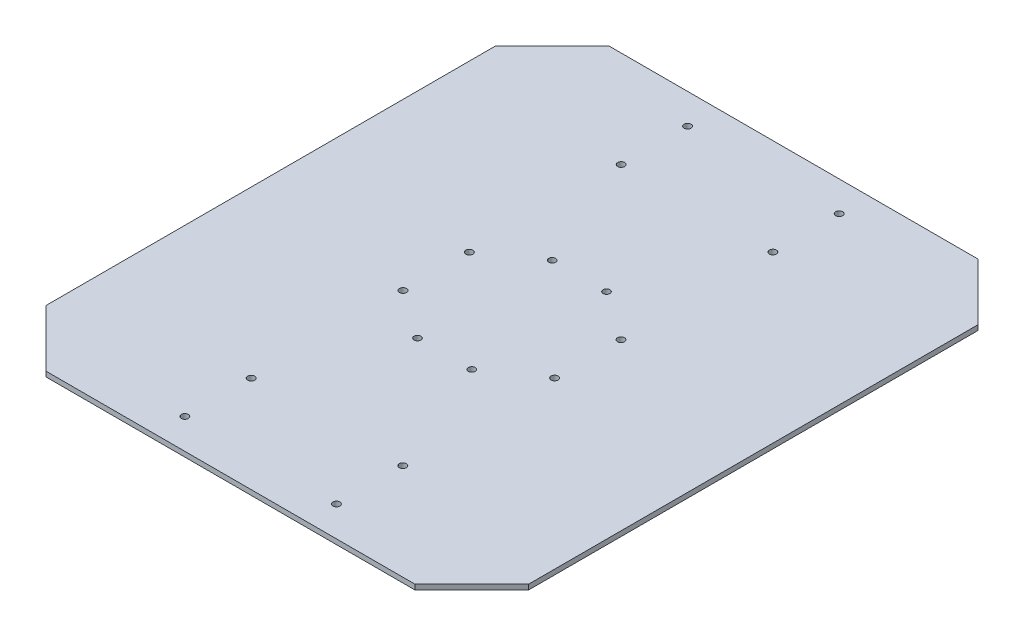
SolidWorks part; units mm, degrees
ref_plane "Front Plane" through (0, 0, 0) normal (0, 0, 1) x (1, 0, 0)
ref_plane "Top Plane" through (0, 0, 0) normal (0, 1, 0) x (1, 0, 0)
ref_plane "Right Plane" through (0, 0, 0) normal (1, 0, 0) x (0, 0, -1)
sketch "Sketch1" plane through (0, 0, 0) normal (0, 1, 0) x (1, 0, 0)
  line L0 (-121.2861, 87.138) -> (-85.365, 123.059)
  line L1 (-121.2861, 123.059) -> (183.5139, 123.059)
  line L2 (-121.2861, 123.059) -> (-121.2861, -232.541)
  line L3 (-121.2861, -232.541) -> (183.5139, -232.541)
  line L4 (183.5139, 123.059) -> (183.5139, -232.541)
  line L5 (31.1139, 95.069) -> (31.1139, -294.9418) construction
  line L6 (-146.0448, -54.741) -> (218.038, -54.741) construction
  line L7 (183.5139, 87.138) -> (147.5929, 123.059)
  line L8 (183.5139, -196.62) -> (147.5929, -232.541)
  line L9 (-121.2861, -196.62) -> (-85.365, -232.541)
  circle A0 centre (-16.7651, 104.009) radius 2.2225
  circle A1 centre (78.9929, 104.009) radius 2.2225
  circle A2 centre (-16.7651, 62.099) radius 2.2225
  circle A3 centre (78.9929, 62.099) radius 2.2225
  circle A4 centre (-16.7651, -171.581) radius 2.2225
  circle A5 centre (78.9929, -171.581) radius 2.2225
  circle A6 centre (78.9929, -213.491) radius 2.2225
  circle A7 centre (-16.7651, -213.491) radius 2.2225
  circle A8 centre (-16.7651, -33.786) radius 2.2225
  circle A9 centre (78.9929, -33.786) radius 2.2225
  circle A10 centre (78.9929, -75.696) radius 2.2225
  circle A11 centre (-16.7651, -75.696) radius 2.2225
  point P8 (31.1139, 123.059)
  point P11 (-121.2861, -54.741)
  point P42 (0, 0)
  point P43 (0, 0)
  point P44 (0, 0)
  point P45 (0, 0)
  point P46 (0, 0)
  point P47 (0, 0)
  dimension "D6" = 95.758
  dimension "D13" = 4.445
  dimension "D1" = 304.8
  dimension "D2" = 355.6
  dimension "D3" = 45
  dimension "D4" = 50.8
  dimension "D5" = 41.91
  dimension "D7" = 104.521
  dimension "D8" = 19.05
  dimension "D9" = 41.91
  dimension "D10" = 20.955
  dimension "D11" = 95.758
  dimension "D12" = 47.879
extrude "Boss-Extrude1" add sketch "Sketch1" along normal blind 3.175
sketch "Sketch2" plane through (0, 3.175, 0) normal (0, 1, 0) x (1, 0, 0)
  line L0 (31.1139, 123.059) -> (31.1139, -287.8465) construction
  line L1 (-85.365, 123.059) -> (147.5929, 123.059) construction
  line L2 (183.5139, -54.741) -> (-158.2106, -54.741) construction
  line L3 (183.5139, 87.138) -> (183.5139, -196.62) construction
  circle A0 centre (13.8419, -12.069) radius 2.159
  circle A1 centre (48.1319, -12.069) radius 2.159
  circle A2 centre (13.8419, -97.159) radius 2.159
  circle A3 centre (48.1319, -97.159) radius 2.159
  dimension "D5" = 4.318
  dimension "D6" = 4.318
  dimension "D7" = 4.318
  dimension "D8" = 4.318
  dimension "D1" = 17.272
  dimension "D2" = 34.29
  dimension "D3" = 85.09
  dimension "D4" = 42.672
extrude "Cut-Extrude1" cut sketch "Sketch2" against normal through all
